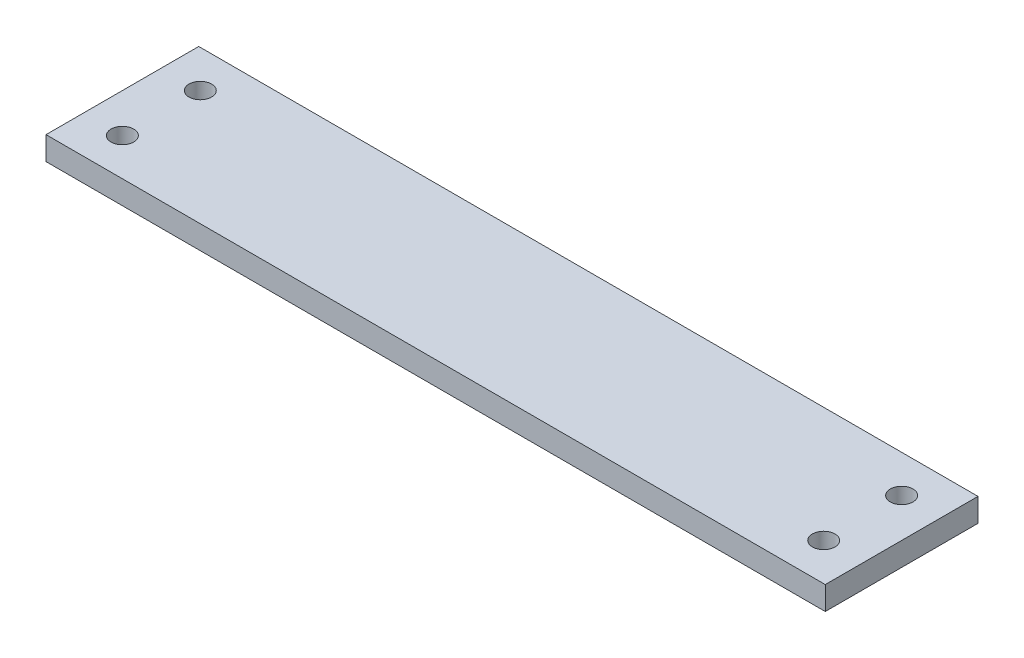
SolidWorks part; units mm, degrees
ref_plane "前视基准面" through (0, 0, 0) normal (0, 0, 1) x (1, 0, 0)
ref_plane "上视基准面" through (0, 0, 0) normal (0, 1, 0) x (1, 0, 0)
ref_plane "右视基准面" through (0, 0, 0) normal (1, 0, 0) x (0, 0, -1)
other "Configuration Table"
sketch "草图1" plane through (0, 0, 0) normal (0, 1, 0) x (1, 0, 0)
  line L1 (0, 0) -> (-100, 0)
  line L2 (0, 0) -> (0, 20)
  line L3 (0, 20) -> (-100, 20)
  line L4 (-100, 0) -> (-100, 20)
  dimension "D1" = 100
  dimension "D2" = 20
extrude "凸台-拉伸1" add sketch "草图1" along normal blind 3
sketch "草图2" plane through (0, 3, 0) normal (0, 1, 0) x (1, 0, 0)
  line L0 (-100, 20) -> (-95, 20) construction
  line L1 (0, 20) -> (-100, 20) construction
  line L2 (-95, 20) -> (-95, 15) construction
  line L3 (-50, 20) -> (-50, -12.4774) construction
  line L4 (-100, 10) -> (-35.9977, 10) construction
  line L5 (-100, 20) -> (-100, 0) construction
  circle A0 centre (-95, 15) radius 1.45
  circle A1 centre (-95, 5) radius 1.45
  circle A2 centre (-5, 5) radius 1.45
  circle A3 centre (-5, 15) radius 1.45
  dimension "D3" = 2.9
  dimension "D1" = 5
  dimension "D2" = 5
extrude "切除-拉伸1" cut sketch "草图2" against normal blind 6
sketch "草图3" plane through (0, 0, 0) normal (0, 0, 1) x (1, 0, 0)
  line L4 (-100, 0) -> (0, 0)
  line L5 (0, 0) -> (0, 3)
  line L6 (0, 3) -> (-100, 3)
  line L7 (-100, 3) -> (-100, 0)
  line L8 (-100, 0) -> (0, 0)
  line L9 (0, 0) -> (0, 3)
  line L10 (0, 3) -> (-100, 3)
  line L11 (-100, 3) -> (-100, 0)
  dimension "D1" = 0
extrude "切除-拉伸2" cut sketch "草图3" against normal blind 0.2
sketch "草图5" plane through (0, 0, -20) normal (0, 0, -1) x (-1, 0, 0)
  line L4 (0, 0) -> (100, 0)
  line L5 (100, 0) -> (100, 3)
  line L6 (100, 3) -> (0, 3)
  line L7 (0, 3) -> (0, 0)
  line L8 (0, 0) -> (100, 0)
  line L9 (100, 0) -> (100, 3)
  line L10 (100, 3) -> (0, 3)
  line L11 (0, 3) -> (0, 0)
  dimension "D1" = 0
extrude "切除-拉伸3" cut sketch "草图5" against normal blind 0.2
